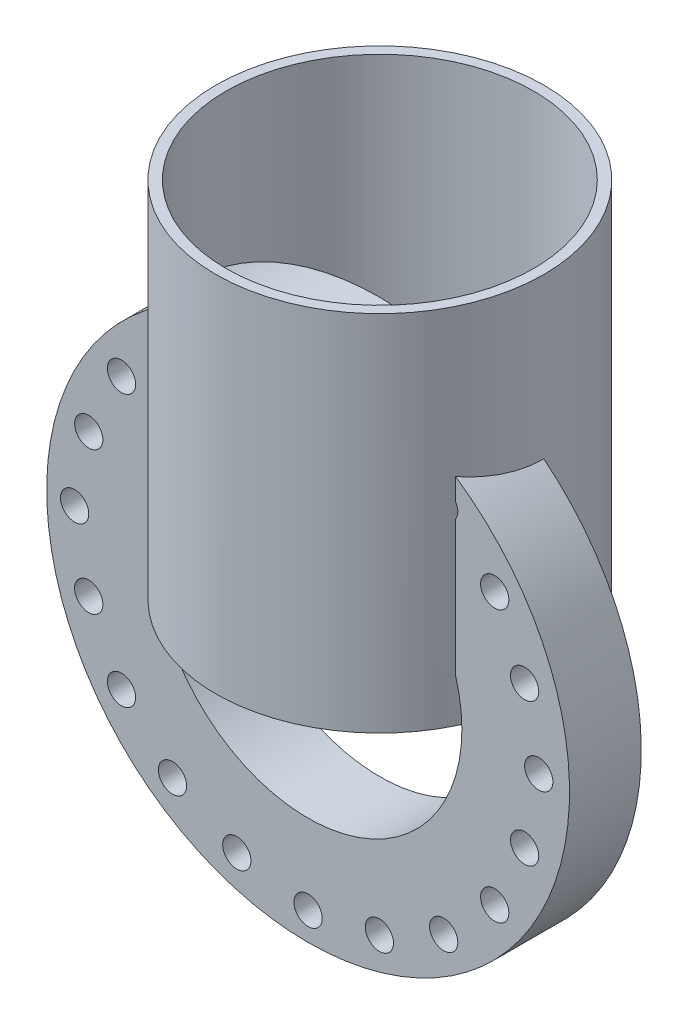
SolidWorks part; units mm, degrees
ref_plane "Front Plane" through (0, 0, 0) normal (0, 0, 1) x (1, 0, 0)
ref_plane "Top Plane" through (0, 0, 0) normal (0, 1, 0) x (1, 0, 0)
ref_plane "Right Plane" through (0, 0, 0) normal (1, 0, 0) x (0, 0, -1)
sketch "Sketch1" plane through (0, 0, 0) normal (0, 1, 0) x (1, 0, 0)
  circle A0 centre (0, 0) radius 203.2
  circle A1 centre (0, 0) radius 190.5
extrude "Boss-Extrude1" add sketch "Sketch1" along normal blind 450
sketch "Sketch2" plane through (0, 0, 0) normal (0, 0, 1) x (1, 0, 0)
  circle A0 centre (0, 0) radius 323.85
  circle A1 centre (0, 0) radius 190.5
  circle A2 centre (285.75, 0) radius 17.5
  circle A3 centre (268.25, 88.3016) radius 17.5
  circle A4 centre (231.1766, 167.9596) radius 17.5
  circle A5 centre (167.9596, 231.1766) radius 17.5
  circle A6 centre (88.3016, 271.7644) radius 17.5
  circle A7 centre (0, 289.2644) radius 17.5
  circle A8 centre (-88.3016, 271.7644) radius 17.5
  circle A9 centre (-167.9596, 231.1766) radius 17.5
  circle A10 centre (-231.1766, 167.9596) radius 17.5
  circle A11 centre (-271.7644, 88.3016) radius 17.5
  circle A12 centre (-289.2644, 0) radius 17.5
  circle A13 centre (-271.7644, -88.3016) radius 17.5
  circle A14 centre (-231.1766, -167.9596) radius 17.5
  circle A15 centre (-167.9596, -231.1766) radius 17.5
  circle A16 centre (-88.3016, -271.7644) radius 17.5
  circle A17 centre (0, -289.2644) radius 17.5
  circle A18 centre (88.3016, -271.7644) radius 17.5
  circle A19 centre (167.9596, -231.1766) radius 17.5
  circle A20 centre (231.1766, -167.9596) radius 17.5
  circle A21 centre (268.25, -88.3016) radius 17.5
extrude "Boss-Extrude2" add sketch "Sketch2" along normal blind 88.9
